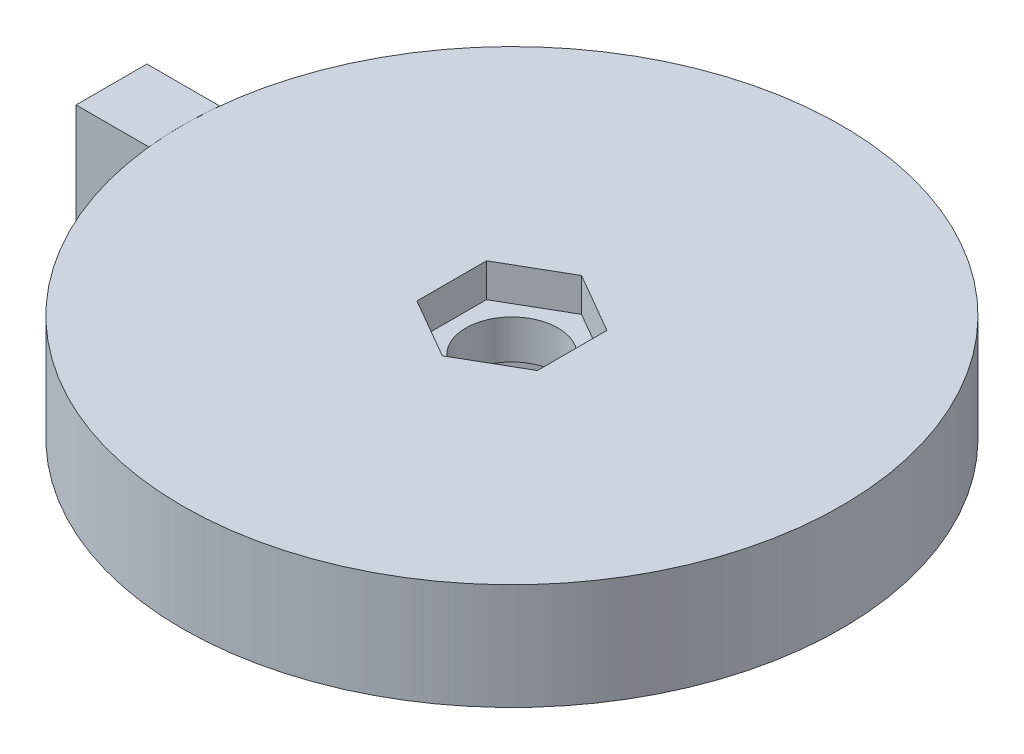
SolidWorks part; units mm, degrees
ref_plane "Plan de face" through (0, 0, 0) normal (0, 0, 1) x (1, 0, 0)
ref_plane "Plan de dessus" through (0, 0, 0) normal (0, 1, 0) x (1, 0, 0)
ref_plane "Plan de droite" through (0, 0, 0) normal (1, 0, 0) x (0, 0, -1)
sketch "Esquisse1" plane through (0, 0, 0) normal (0, 1, 0) x (1, 0, 0)
  circle A0 centre (0, 0) radius 46.5
  dimension "D1" = 93
extrude "Boss.-Extru.1" add sketch "Esquisse1" along normal blind 15
sketch "Esquisse2" plane through (0, 0, 0) normal (0, -1, 0) x (1, 0, 0)
  line L0 (-46.5, 0) -> (-56.5, 0)
  line L1 (-56.5, 0) -> (-56.5, -5)
  line L2 (-56.5, 0) -> (-56.5, 5)
  line L3 (-56.5, 5) -> (-46.2304, 5)
  line L4 (-56.5, -5) -> (-46.2304, -5)
  line L5 (-46.2304, -5) -> (-46.2304, 5)
  circle A0 centre (0, 0) radius 46.5 construction
  circle M4 centre (0, 0) radius 46.5
  dimension "D1" = 10
  dimension "D2" = 5
extrude "Boss.-Extru.2" add sketch "Esquisse2" against normal blind 15 separate body contours L1 L4 L0 M4 | L3 L2 L0 M4
sketch "Esquisse3" plane through (0, 15, 0) normal (0, 1, 0) x (1, 0, 0)
  circle A0 centre (0, 0) radius 6.5
  dimension "D1" = 13
extrude "Enlèv. mat.-Extru.1" cut sketch "Esquisse3" against normal through all contours A0
sketch "Esquisse4" plane through (0, 15, 0) normal (0, 1, 0) x (1, 0, 0)
  line L12 (-4, 6.9282) -> (-8, 4.6188)
  line L13 (-8, 4.6188) -> (-8, 0)
  line L14 (-8, 0) -> (-8, -4.6188)
  line L15 (-8, -4.6188) -> (-4, -6.9282)
  line L16 (-4, -6.9282) -> (0, -9.2376)
  line L17 (0, -9.2376) -> (4, -6.9282)
  line L18 (4, -6.9282) -> (8, -4.6188)
  line L19 (8, -4.6188) -> (8, 0)
  line L20 (8, 0) -> (8, 4.6188)
  line L21 (8, 4.6188) -> (4, 6.9282)
  line L22 (4, 6.9282) -> (0, 9.2376)
  line L23 (0, 9.2376) -> (-4, 6.9282)
  line L24 (4.25, 7.3612) -> (0, 9.815)
  line L25 (0, 9.815) -> (-4.25, 7.3612)
  line L26 (-4.25, 7.3612) -> (-8.5, 4.9075)
  line L27 (-8.5, 4.9075) -> (-8.5, 0)
  line L28 (-8.5, 0) -> (-8.5, -4.9075)
  line L29 (-8.5, -4.9075) -> (-4.25, -7.3612)
  line L30 (-4.25, -7.3612) -> (0, -9.815)
  line L31 (0, -9.815) -> (4.25, -7.3612)
  line L32 (4.25, -7.3612) -> (8.5, -4.9075)
  line L33 (8.5, -4.9075) -> (8.5, 0)
  line L34 (8.5, 0) -> (8.5, 4.9075)
  line L35 (8.5, 4.9075) -> (4.25, 7.3612)
  dimension "D1" = 0.5
extrude "Enlèv. mat.-Extru.3" cut sketch "Esquisse4" against normal blind 4.75 contours L35 L24 L25 L26 L27 L28 L29 L30 L31 L32 L33 L34
sketch "Esquisse5" plane through (0, 0, 0) normal (0, -1, 0) x (1, 0, 0)
  line L0 (-8.5, 4.9075) -> (0, 9.815) construction
  line L1 (0, 9.815) -> (8.5, 4.9075) construction
  line L2 (8.5, 4.9075) -> (8.5, -4.9075) construction
  line L3 (8.5, -4.9075) -> (0, -9.815) construction
  line L4 (0, -9.815) -> (-8.5, -4.9075) construction
  line L5 (-8.5, -4.9075) -> (-8.5, 4.9075) construction
  line L6 (-8.5, 4.9075) -> (0, 9.815)
  line L7 (0, 9.815) -> (8.5, 4.9075)
  line L8 (8.5, 4.9075) -> (8.5, -4.9075)
  line L9 (8.5, -4.9075) -> (0, -9.815)
  line L10 (0, -9.815) -> (-8.5, -4.9075)
  line L11 (-8.5, -4.9075) -> (-8.5, 4.9075)
extrude "Enlèv. mat.-Extru.4" cut sketch "Esquisse5" against normal blind 4.75 contours L11 L6 L7 L8 L9 L10
sketch "Esquisse6" plane through (0, 0, 0) normal (0, -1, 0) x (1, 0, 0)
  circle A0 centre (0, 0) radius 46.5
